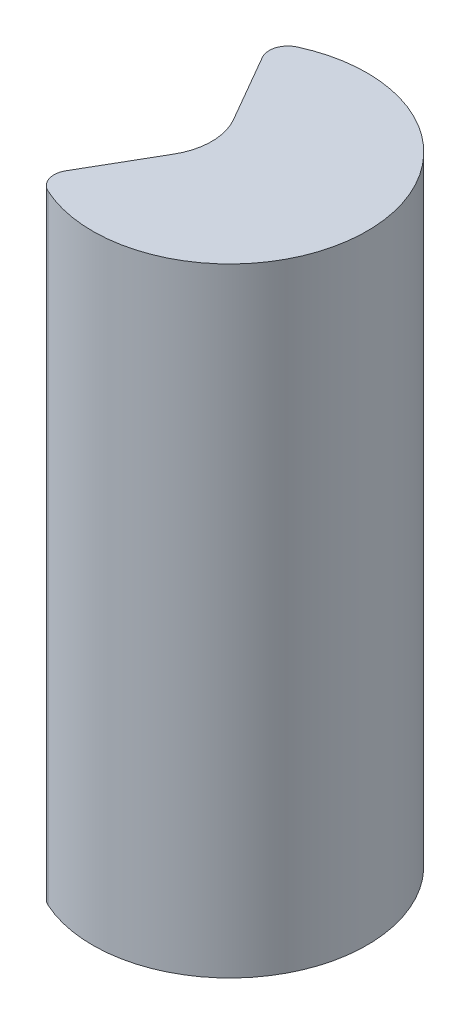
SolidWorks part; units mm, degrees
ref_plane "Front Plane" through (0, 0, 0) normal (0, 0, 1) x (1, 0, 0)
ref_plane "Top Plane" through (0, 0, 0) normal (0, 1, 0) x (1, 0, 0)
ref_plane "Right Plane" through (0, 0, 0) normal (1, 0, 0) x (0, 0, -1)
sketch "Sketch1" plane through (0, 0, 0) normal (0, 1, 0) x (1, 0, 0)
  line L0 (-13.9537, 15.875) -> (-35.0554, 52.4242)
  line L3 (-13.9537, -15.875) -> (-35.0554, -52.4242)
  line L4 (-87.2562, 0) -> (100.2653, 0) construction
  arc A3 (-30.5716, -66.5103) -> (-30.5716, 66.5103) centre (0, 0) ccw
  arc A4 (-13.9537, -15.875) -> (-13.9537, 15.875) centre (-41.45, 0) ccw
  arc A5 (-30.5716, -66.5103) -> (-35.0554, -52.4242) centre (-26.3951, -57.4242) cw
  arc A6 (-30.5716, 66.5103) -> (-35.0554, 52.4242) centre (-26.3951, 57.4242) ccw
  point P4 (-73.2, 0)
  dimension "D3" = 120
  dimension "D1" = 146.4
  dimension "D2" = 63.5
  dimension "D6" = 10
  dimension "D4" = 73.2
  dimension "D5" = 60
extrude "Boss-Extrude1" add sketch "Sketch1" along normal blind 330
